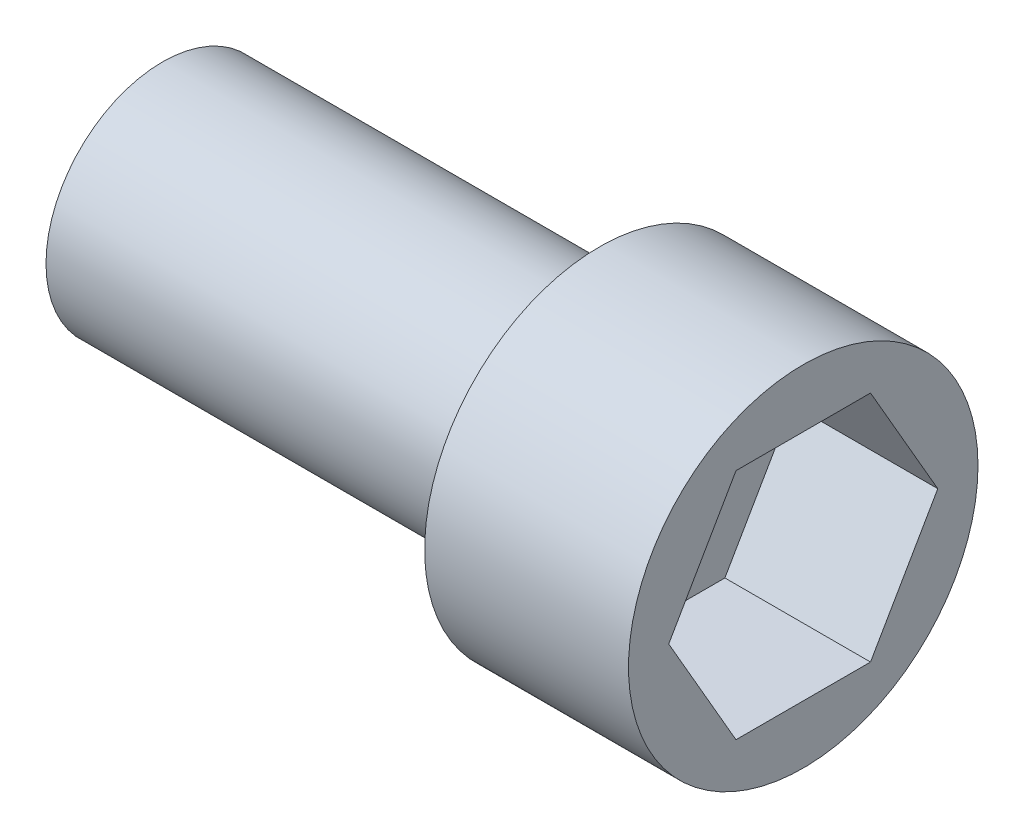
SolidWorks part; units mm, degrees
material "AISI 1010 Steel, hot rolled bar"
ref_plane "Front Plane" through (0, 0, 0) normal (0, 0, 1) x (1, 0, 0)
ref_plane "Top Plane" through (0, 0, 0) normal (0, 1, 0) x (1, 0, 0)
ref_plane "Right Plane" through (0, 0, 0) normal (1, 0, 0) x (0, 0, -1)
sketch "Sketch1" plane through (0, 0, 0) normal (0, 0, 1) x (1, 0, 0)
  line L0 (0, 0) -> (0, 4)
  line L1 (0, 4) -> (15, 4)
  line L2 (15, 4) -> (15, 6)
  line L3 (15, 6) -> (22, 6)
  line L4 (22, 6) -> (22, 0)
  line L5 (22, 0) -> (0, 0)
  dimension "D1" = 22
  dimension "D2" = 4
  dimension "D3" = 15
  dimension "D4" = 6
revolve "Revolve2" add sketch "Sketch1" angle 360 about L5
sketch "Sketch2" plane through (22, 0, 0) normal (1, 0, 0) x (0, 0, -1)
  line L1 (4.6188, 0) -> (2.3094, 4)
  line L2 (2.3094, 4) -> (-2.3094, 4)
  line L3 (-2.3094, 4) -> (-4.6188, 0)
  line L4 (-4.6188, 0) -> (-2.3094, -4)
  line L5 (-2.3094, -4) -> (2.3094, -4)
  line L6 (2.3094, -4) -> (4.6188, 0)
  circle A0 centre (0, 0) radius 4 construction
  dimension "D1" = 8
extrude "Cut-Extrude1" cut sketch "Sketch2" against normal blind 5
